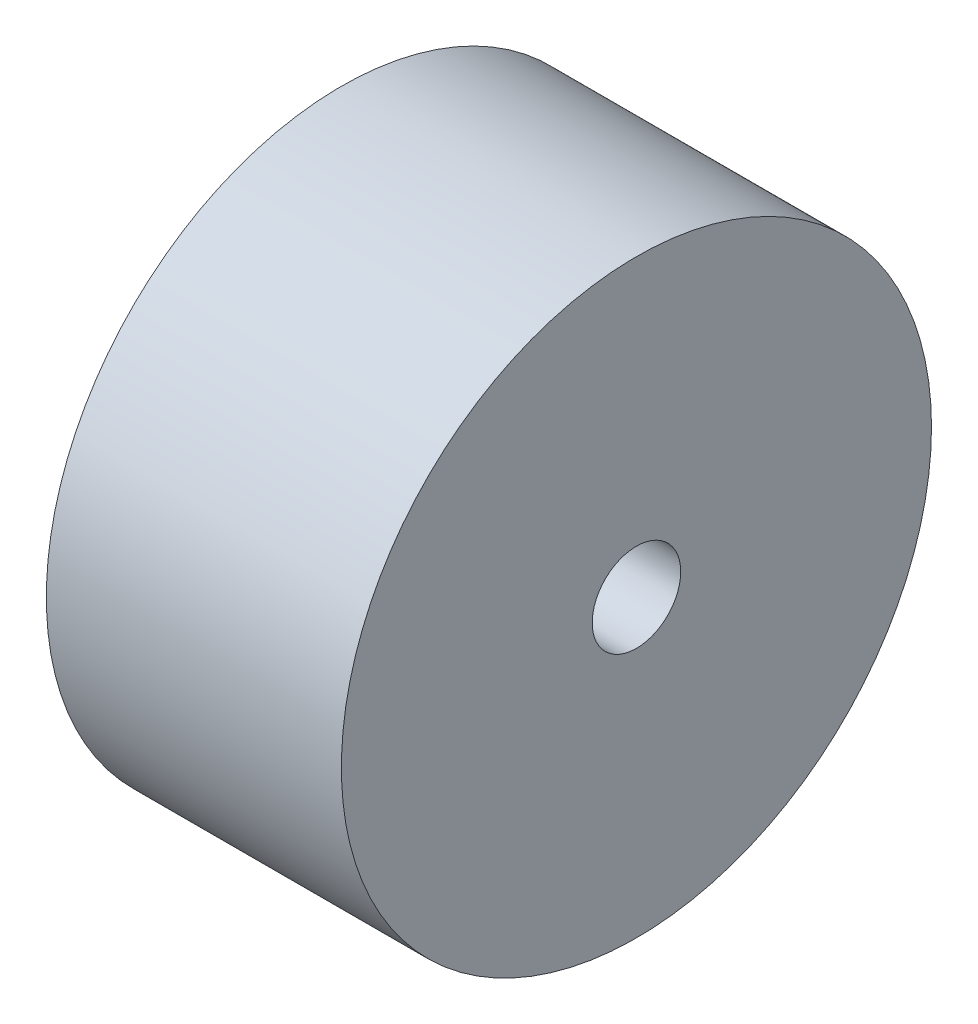
SolidWorks part; units mm, degrees
ref_plane "前视基准面" through (0, 0, 0) normal (0, 0, 1) x (1, 0, 0)
ref_plane "上视基准面" through (0, 0, 0) normal (0, 1, 0) x (1, 0, 0)
ref_plane "右视基准面" through (0, 0, 0) normal (1, 0, 0) x (0, 0, -1)
sketch "Sketch2" plane through (0, 0, 0) normal (1, 0, 0) x (0, 0, -1)
  circle A0 centre (0, 0) radius 20
  circle A1 centre (0, 0) radius 3
  dimension "D1" = 40
  dimension "D2" = 6
extrude "Boss-Extrude1" add sketch "Sketch2" along normal blind 20
